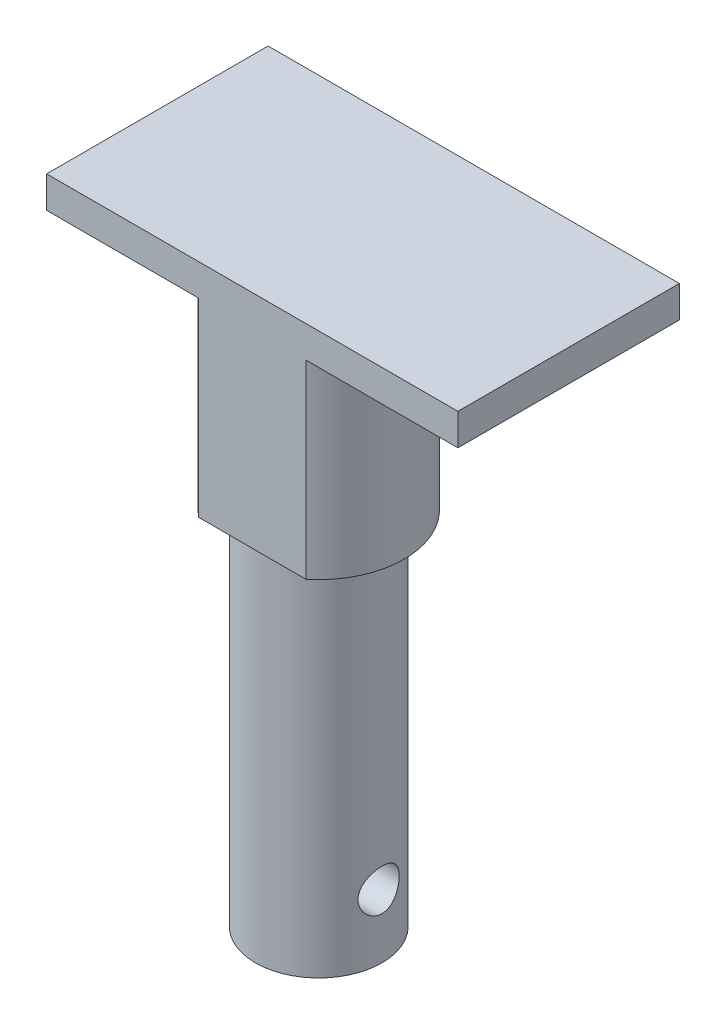
SolidWorks part; units mm, degrees
ref_plane "정면" through (0, 0, 0) normal (0, 0, 1) x (1, 0, 0)
ref_plane "윗면" through (0, 0, 0) normal (0, 1, 0) x (1, 0, 0)
ref_plane "우측면" through (0, 0, 0) normal (1, 0, 0) x (0, 0, -1)
sketch "스케치1" plane through (0, 0, 0) normal (0, 1, 0) x (1, 0, 0)
  circle A0 centre (0, 0) radius 10
  dimension "D1" = 20
extrude "보스-돌출1" add sketch "스케치1" along normal blind 57
sketch "스케치2" plane through (0, 57, 0) normal (0, 1, 0) x (1, 0, 0)
  circle A0 centre (0, 0) radius 13.5
  dimension "D1" = 27
extrude "보스-돌출2" add sketch "스케치2" along normal blind 30
sketch "스케치7" plane through (0, 0, 0) normal (1, 0, 0) x (0, 0, -1)
  circle A0 centre (0, 10) radius 3.25
  dimension "D1" = 6.5
  dimension "D2" = 10
extrude "컷-돌출1" cut sketch "스케치7" against normal through all both and the other way through all
sketch "스케치8" plane through (0, 87, 0) normal (0, 1, 0) x (1, 0, 0)
  line L5 (-13.5, -16.5) -> (13.5, -16.5)
  line L6 (-13.5, -16.5) -> (-13.5, -10.5)
  line L7 (-13.5, -10.5) -> (13.5, -10.5)
  line L8 (13.5, -16.5) -> (13.5, -10.5)
  line L9 (-13.5, -16.5) -> (13.5, -10.5) construction
  line L10 (-13.5, -10.5) -> (13.5, -16.5) construction
  point P0 (0, -13.5)
  dimension "D2" = 6
  dimension "D1" = 13.5
  dimension "D3" = 27
extrude "컷-돌출2" cut sketch "스케치8" against normal through all contours L5 L8 L7 L6
sketch "스케치9" plane through (0, 87, 0) normal (0, 1, 0) x (1, 0, 0)
  line L0 (-8.4853, -10.5) -> (8.4853, -10.5) construction
  line L1 (-32.5, 24.5) -> (32.5, 24.5)
  line L2 (-32.5, 24.5) -> (-32.5, -10.5)
  line L3 (-32.5, -10.5) -> (32.5, -10.5)
  line L4 (32.5, 24.5) -> (32.5, -10.5)
  point P4 (0, -10.5)
  dimension "D1" = 65
  dimension "D2" = 35
extrude "보스-돌출3" add sketch "스케치9" along normal blind 5
